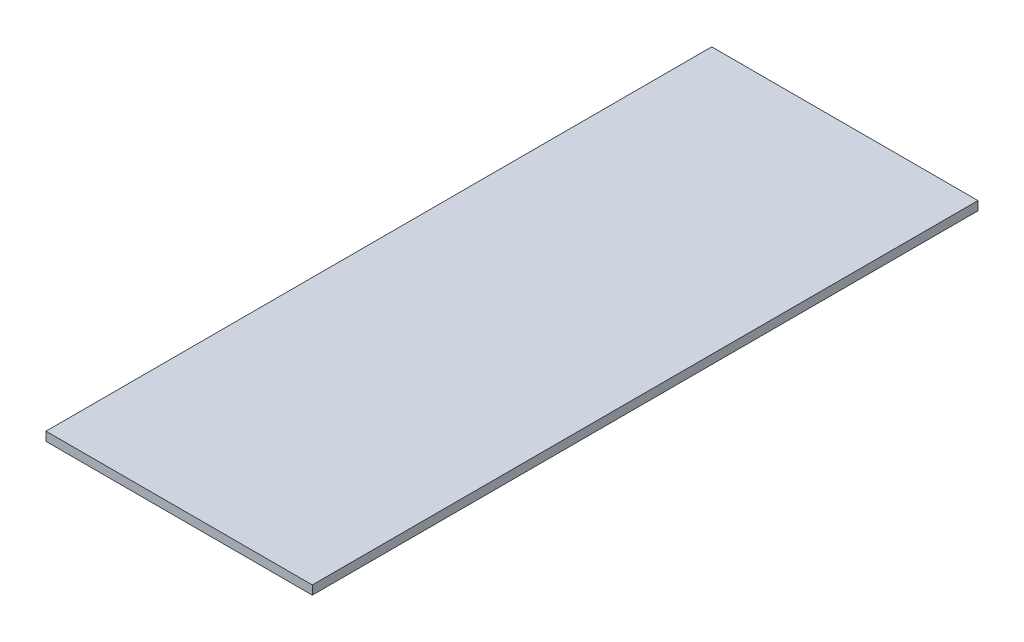
SolidWorks part; units mm, degrees
ref_plane "Alzado" through (0, 0, 0) normal (0, 0, 1) x (1, 0, 0)
ref_plane "Planta" through (0, 0, 0) normal (0, 1, 0) x (1, 0, 0)
ref_plane "Vista lateral" through (0, 0, 0) normal (1, 0, 0) x (0, 0, -1)
sketch "Croquis1" plane through (0, 0, 0) normal (0, 1, 0) x (1, 0, 0)
  line L1 (-150, 375) -> (150, 375)
  line L2 (-150, 375) -> (-150, -375)
  line L3 (-150, -375) -> (150, -375)
  line L4 (150, 375) -> (150, -375)
  line L5 (-150, 375) -> (150, -375) construction
  line L6 (-150, -375) -> (150, 375) construction
  point P0 (0, 0)
  dimension "D1" = 300
  dimension "D2" = 750
extrude "Saliente-Extruir1" add sketch "Croquis1" along normal blind 10
